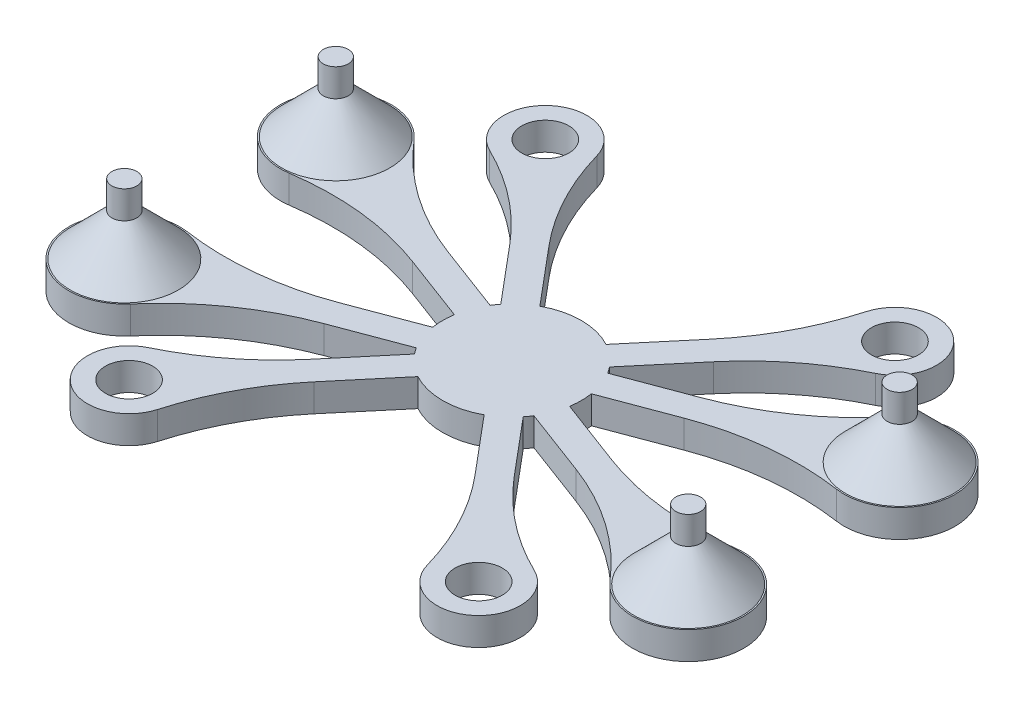
SolidWorks part; units mm, degrees
ref_plane "Front Plane" through (0, 0, 0) normal (0, 0, 1) x (1, 0, 0)
ref_plane "Top Plane" through (0, 0, 0) normal (0, 1, 0) x (1, 0, 0)
ref_plane "Right Plane" through (0, 0, 0) normal (1, 0, 0) x (0, 0, -1)
sketch "Sketch1" plane through (0, 0, 0) normal (0, 1, 0) x (1, 0, 0)
  line L0 (-1, 19) -> (44.2, 19) construction
  line L1 (0, 0) -> (43.2, 0) construction
  line L2 (0, 0) -> (0, 18) construction
  line L3 (0, 18) -> (43.2, 18) construction
  line L4 (43.2, 0) -> (43.2, 18) construction
  line L5 (1.28, 16.62) -> (41.92, 16.62) construction
  line L6 (1.28, 16.62) -> (1.28, 1.38) construction
  line L7 (1.28, 1.38) -> (41.92, 1.38) construction
  line L8 (41.92, 16.62) -> (41.92, 1.38) construction
  line L9 (44.2, -1) -> (44.2, 19) construction
  line L10 (-1, -1) -> (44.2, -1) construction
  line L11 (-1, -1) -> (-1, 19) construction
  line L12 (21.6, 19) -> (21.6, -1) construction
  line L13 (34.2, -6) -> (34.2, 24) construction
  line L14 (9, -6) -> (9, 24) construction
  line L15 (21.6, 9) -> (10.9296, 21.7029) construction
  line L16 (-1, 9) -> (44.2, 9) construction
  line L17 (21.6, 9) -> (32.2704, 21.7029) construction
  line L18 (21.6, 9) -> (38.1747, 15.2155) construction
  line L19 (21.6, 9) -> (38.1747, 2.7845) construction
  line L20 (24.8162, 11.2741) -> (33.1465, 21.1911)
  line L22 (21.6, 10.5547) -> (11.5849, 22.4775)
  line L24 (21.6, 9) -> (32.2704, -3.7029) construction
  line L25 (21.6, 9) -> (5.0253, 15.2155) construction
  line L26 (21.6, 9) -> (5.0253, 2.7845) construction
  line L27 (21.6, 9) -> (10.9296, -3.7029) construction
  line L28 (24.448, 9) -> (38.6447, 14.3238)
  line L29 (24.8162, 6.7259) -> (37.9425, 1.8036)
  line L33 (24.448, 9) -> (38.6447, 3.6762)
  line L34 (21.6, 7.4453) -> (11.5849, -4.4775)
  line L35 (21.6, 7.4453) -> (31.6151, -4.4775)
  line L38 (24.8162, 11.2741) -> (37.9425, 16.1964)
  line L40 (24.8162, 6.7259) -> (33.1465, -3.1911)
  line L42 (18.3838, 6.7259) -> (5.2575, 1.8036)
  line L45 (21.2489, 9.9363) -> (41.5689, 17.5563) construction
  line L48 (21.6, 9) -> (41.92, 16.62) construction
  line L52 (22.3657, 9.6432) -> (34.9657, -5.3568) construction
  line L53 (21.6, 9) -> (34.2, -6) construction
  line L58 (21.9511, 8.0637) -> (1.6311, 0.4437) construction
  line L60 (21.6, 9) -> (1.28, 1.38) construction
  line L61 (21.6, 10.5547) -> (31.6151, 22.4775)
  line L65 (18.3838, 11.2741) -> (5.2575, 16.1964)
  line L66 (18.3838, 11.2741) -> (10.0535, 21.1911)
  line L67 (18.752, 9) -> (4.5553, 3.6762)
  line L68 (18.752, 9) -> (4.5553, 14.3238)
  line L69 (18.3838, 6.7259) -> (10.0535, -3.1911)
  circle A0 centre (1.28, 16.62) radius 0.9
  circle A1 centre (41.92, 16.62) radius 0.9
  circle A2 centre (1.28, 1.38) radius 0.9
  circle A3 centre (41.92, 1.38) radius 0.9
  arc A4 (33.1465, 21.1911) -> (31.6151, 22.4775) centre (34.2, 24) ccw
  arc A5 (33.1465, -3.1911) -> (31.6151, -4.4775) centre (34.2, -6) cw
  arc A6 (10.0535, -3.1911) -> (11.5849, -4.4775) centre (9, -6) ccw
  arc A7 (10.0535, 21.1911) -> (11.5849, 22.4775) centre (9, 24) cw
  arc A8 (37.9425, 1.8036) -> (38.6447, 3.6762) centre (41.92, 1.38) ccw
  arc A9 (38.6447, 14.3238) -> (37.9425, 16.1964) centre (41.92, 16.62) ccw
  arc A10 (5.2575, 16.1964) -> (4.5553, 14.3238) centre (1.28, 16.62) ccw
  arc A11 (4.5553, 3.6762) -> (5.2575, 1.8036) centre (1.28, 1.38) ccw
  circle A12 centre (21.6, 9) radius 5
  point P30 (0, 0)
  point P31 (0, 0)
  point P33 (0, 0)
  dimension "D7" = 1.8
  dimension "D8" = 1.8
  dimension "D9" = 1.8
  dimension "D10" = 1.8
  dimension "D15" = 6
  dimension "D16" = 2
  dimension "D11" = 8
  dimension "D18" = 10
  dimension "D1" = 18
  dimension "D2" = 43.2
  dimension "D3" = 15.24
  dimension "D4" = 40.64
  dimension "D5" = 1.28
  dimension "D6" = 1.38
  dimension "D12" = 30
  dimension "D13" = 5
  dimension "D14" = 10
  dimension "D19" = 1
  dimension "D17" = 2
extrude "Boss-Extrude1" add sketch "Sketch1" along normal blind 2 contours L61 A12 L22 | L66 A12 L65 | L68 A12 L67 | L38 A12 L20 | L33 A12 L28 | L40 A12 L29 | L34 A12 L35 | L42 A12 L69
fillet "Fillet1" radius 20 16 edges at (5.2575, 1, -1.8036) (4.5553, 1, -3.6762) (11.5849, 1, 4.4775) (10.0535, 1, 3.1911) (33.1465, 1, 3.1911) (31.6151, 1, 4.4775) (37.9425, 1, -1.8036) (38.6447, 1, -3.6762) (38.6447, 1, -14.3238) (37.9425, 1, -16.1964) (31.6151, 1, -22.4775) (33.1465, 1, -21.1911) (10.0535, 1, -21.1911) (11.5849, 1, -22.4775) (5.2575, 1, -16.1964) (4.5553, 1, -14.3238)
sketch "Sketch3" plane through (0, 2, 0) normal (0, 1, 0) x (1, 0, 0)
  point P0 (9, -6)
  point P2 (34.2, -6)
  point P4 (34.2, 24)
  point P6 (9, 24)
hole_wizard "M3 Clearance Hole2" positions "Sketch3" profile "Sketch4" hole size "M3" standard "ISO" end condition through all
sketch "Sketch4" plane through (9, 2, 6) normal (1, 0, 0) x (0, 0, 1)
  line L0 (0, 0) -> (0, 2)
  line L1 (0, 2) -> (1.7, 2)
  line L2 (1.7, 2) -> (1.7, 0)
  line L5 (1.7, 0) -> (0, 0)
  line L11 (0, -6.35) -> (0, 107.95) construction
  dimension "Thru Hole Dia." = 3.4
  dimension "Thru Hole Depth" = 2
sketch "Sketch5" plane through (0, 2, 0) normal (0, 1, 0) x (1, 0, 0)
  circle A0 centre (41.92, 1.38) radius 0.9 construction
  circle A1 centre (41.92, 16.62) radius 0.9 construction
  circle A2 centre (1.28, 16.62) radius 0.9 construction
  circle A3 centre (1.28, 1.38) radius 0.9 construction
  circle A4 centre (41.92, 1.38) radius 0.9
  circle A5 centre (41.92, 16.62) radius 0.9
  circle A6 centre (1.28, 16.62) radius 0.9
  circle A7 centre (1.28, 1.38) radius 0.9
  point P0 (41.92, 16.62)
  point P2 (41.92, 1.38)
  point P4 (1.28, 1.38)
  point P18 (0, 0)
extrude "Boss-Extrude2" add sketch "Sketch5" along normal blind 5 contours A7 | A4 | A5 | A6
chamfer "Chamfer1" distance 3 angle 45 4 edges at (41.92, 2, -15.72) (41.92, 2, -0.48) (1.28, 2, -0.48) (1.28, 2, -15.72)
